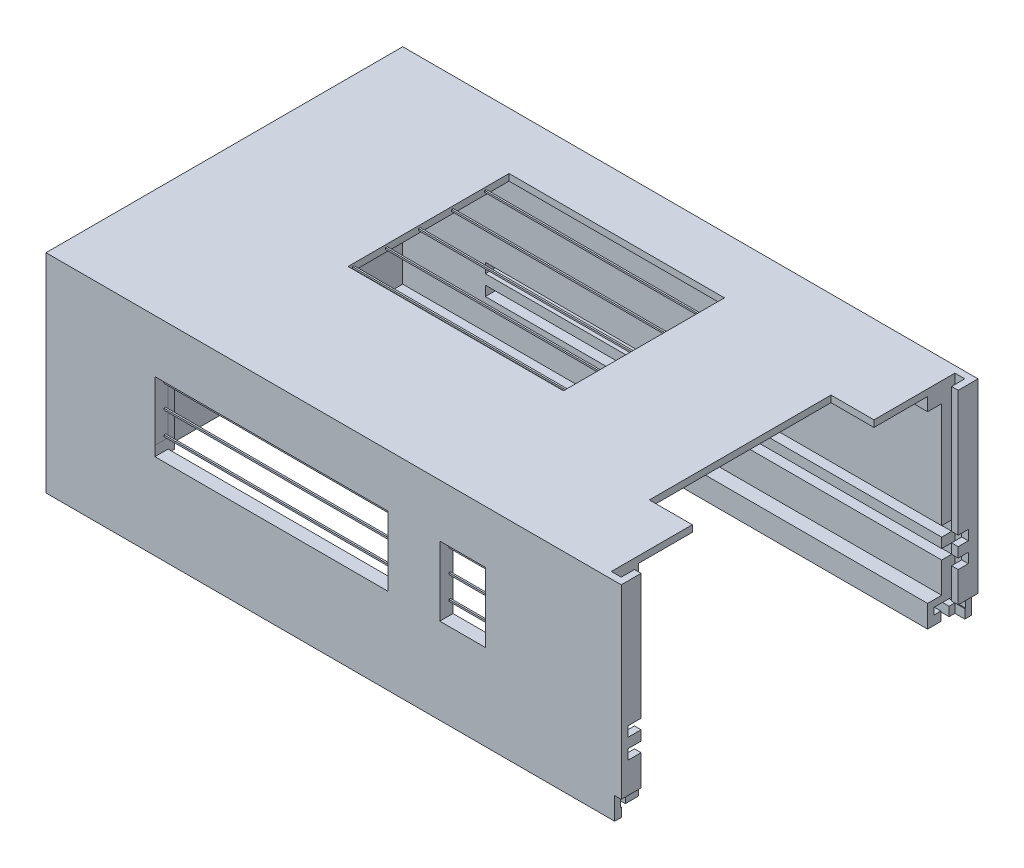
SolidWorks part; units mm, degrees
ref_plane "정면" through (0, 0, 0) normal (0, 0, 1) x (1, 0, 0)
ref_plane "윗면" through (0, 0, 0) normal (0, 1, 0) x (1, 0, 0)
ref_plane "우측면" through (0, 0, 0) normal (1, 0, 0) x (0, 0, -1)
sketch "스케치1" plane through (0, 0, 0) normal (0, 1, 0) x (1, 0, 0)
  line L1 (-87.075, 54) -> (87.075, 54)
  line L2 (-87.075, 54) -> (-87.075, -54)
  line L3 (-87.075, -54) -> (87.075, -54)
  line L4 (87.075, 54) -> (87.075, -54)
  line L5 (-87.075, 54) -> (87.075, -54) construction
  line L6 (-87.075, -54) -> (87.075, 54) construction
  point P0 (0, 0)
  dimension "D1" = 174.15
  dimension "D2" = 108
extrude "보스-돌출1" add sketch "스케치1" along normal blind 63
sketch "스케치4" plane through (87.075, 0, 0) normal (1, 0, 0) x (0, 0, -1)
  line L0 (-50, 0) -> (-50, 3)
  line L1 (-54, 0) -> (54, 0) construction
  line L2 (-50, 3) -> (-52, 3)
  line L3 (-52, 3) -> (-52, 4.5)
  line L4 (-52, 4.5) -> (-46, 4.5)
  line L5 (-46, 4.5) -> (-46, 3)
  line L6 (-46, 3) -> (-48, 3)
  line L7 (-48, 3) -> (-48, 0)
  line L8 (-48, 0) -> (-50, 0)
  line L10 (-54, 63) -> (-54, 0) construction
  line L11 (-50.25, 0) -> (-50.25, 2.75)
  line L12 (-50.25, 2.75) -> (-52.25, 2.75)
  line L13 (-52.25, 2.75) -> (-52.25, 4.75)
  line L14 (-52.25, 4.75) -> (-45.75, 4.75)
  line L15 (-45.75, 4.75) -> (-45.75, 2.75)
  line L16 (-45.75, 2.75) -> (-47.75, 2.75)
  line L17 (-47.75, 2.75) -> (-47.75, 0)
  line L18 (-50, 0) -> (-50.25, 0)
  line L19 (-48, 0) -> (-47.75, 0)
  dimension "D1" = 3
  dimension "D2" = 2
  dimension "D3" = 2
  dimension "D4" = 6
  dimension "D5" = 2
  dimension "D6" = 1.5
  dimension "D7" = 1.5
  dimension "D8" = 0.25
sketch "스케치5" plane through (-87.075, 0, 0) normal (-1, 0, 0) x (0, 0, 1)
  line L0 (50, 0) -> (50, 3) construction
  line L1 (50, 3) -> (52, 3) construction
  line L2 (52, 3) -> (52, 4.5) construction
  line L3 (52, 4.5) -> (46, 4.5) construction
  line L4 (46, 4.5) -> (46, 3) construction
  line L5 (46, 3) -> (48, 3) construction
  line L6 (48, 3) -> (48, 0) construction
  line L7 (48, 0) -> (50, 0) construction
  line L8 (50, 0) -> (50.25, 0) construction
  line L9 (50.25, 0) -> (50.25, 2.75) construction
  line L10 (50.25, 2.75) -> (52.25, 2.75) construction
  line L11 (52.25, 2.75) -> (52.25, 4.75) construction
  line L12 (52.25, 4.75) -> (45.75, 4.75) construction
  line L13 (45.75, 4.75) -> (45.75, 2.75) construction
  line L14 (45.75, 2.75) -> (47.75, 2.75) construction
  line L15 (47.75, 2.75) -> (47.75, 0) construction
  line L16 (48, 0) -> (47.75, 0) construction
  line L17 (50, 0) -> (50, 3)
  line L18 (50, 3) -> (52, 3)
  line L19 (52, 3) -> (52, 4.5)
  line L20 (52, 4.5) -> (46, 4.5)
  line L21 (46, 4.5) -> (46, 3)
  line L22 (46, 3) -> (48, 3)
  line L23 (48, 3) -> (48, 0)
  line L24 (48, 0) -> (50, 0)
  line L25 (50, 0) -> (50.25, 0)
  line L26 (50.25, 0) -> (50.25, 2.75)
  line L27 (50.25, 2.75) -> (52.25, 2.75)
  line L28 (52.25, 2.75) -> (52.25, 4.75)
  line L29 (52.25, 4.75) -> (45.75, 4.75)
  line L30 (45.75, 4.75) -> (45.75, 2.75)
  line L31 (45.75, 2.75) -> (47.75, 2.75)
  line L32 (47.75, 2.75) -> (47.75, 0)
  line L33 (48, 0) -> (47.75, 0)
  line L34 (0, 0) -> (0, 63) construction
  line L35 (-54, 63) -> (54, 63) construction
  line L36 (-48, 0) -> (-47.75, 0)
  line L37 (-47.75, 2.75) -> (-47.75, 0)
  line L38 (-45.75, 2.75) -> (-47.75, 2.75)
  line L39 (-45.75, 4.75) -> (-45.75, 2.75)
  line L40 (-52.25, 4.75) -> (-45.75, 4.75)
  line L41 (-52.25, 2.75) -> (-52.25, 4.75)
  line L42 (-50.25, 2.75) -> (-52.25, 2.75)
  line L43 (-50.25, 0) -> (-50.25, 2.75)
  line L44 (-50, 0) -> (-50.25, 0)
  line L45 (-48, 0) -> (-50, 0)
  line L46 (-48, 3) -> (-48, 0)
  line L47 (-46, 3) -> (-48, 3)
  line L48 (-46, 4.5) -> (-46, 3)
  line L49 (-52, 4.5) -> (-46, 4.5)
  line L50 (-52, 3) -> (-52, 4.5)
  line L51 (-50, 3) -> (-52, 3)
  line L52 (-50, 0) -> (-50, 3)
  line M2 (-54, 0) -> (54, 0)
extrude "컷-돌출2" cut sketch "스케치5" against normal up to surface (174.15 mm away) contours L52 L51 L50 L49 L48 L47 L46 L37 L38 L39 L40 L41 L42 L43 M2 | L52 L46 L47 L48 L49 L50 L51 M2 | L31 L32 L23 L22 L21 L20 L19 L18 L17 L26 L27 L28 L29 L30 M2 | L22 L23 L17 L18 L19 L20 L21 M2 up to face at (87.075, 31.5, 0)
sketch "스케치6" plane through (0, 0, 0) normal (0, -1, 0) x (1, 0, 0)
  line L0 (87.075, -54) -> (-87.075, -54) construction
  line L1 (-87.075, 54) -> (-85.075, 54)
  line L2 (-87.075, 54) -> (-87.075, -54)
  line L3 (-87.075, -54) -> (-85.075, -54)
  line L4 (-85.075, 54) -> (-85.075, -54)
  dimension "D1" = 2
extrude "컷-돌출3" cut sketch "스케치6" against normal up to surface (4.75 mm away) up to face at (0, 4.75, 49)
sketch "스케치7" plane through (87.075, 0, 0) normal (1, 0, 0) x (0, 0, -1)
  line L0 (-54, 63) -> (-54, 0) construction
  line L1 (-48, 57) -> (48, 57)
  line L2 (-48, 57) -> (-48, 6.75)
  line L3 (-48, 6.75) -> (48, 6.75)
  line L4 (48, 57) -> (48, 6.75)
  line L5 (54, 63) -> (54, 0) construction
  line L6 (45.75, 4.75) -> (52.25, 4.75) construction
  line L7 (-54, 63) -> (54, 63) construction
  dimension "D1" = 6
  dimension "D2" = 6
  dimension "D3" = 2
  dimension "D4" = 6
extrude "컷-돌출5" cut sketch "스케치7" against normal blind 168.15
sketch "스케치8" plane through (87.075, 0, 0) normal (1, 0, 0) x (0, 0, -1)
  line L0 (-48, 6.75) -> (48, 6.75) construction
  line L1 (-43.75, 6.75) -> (43.75, 6.75)
  line L2 (-43.75, 6.75) -> (-43.75, 2)
  line L3 (-43.75, 2) -> (43.75, 2)
  line L4 (43.75, 6.75) -> (43.75, 2)
  line L5 (-45.75, 2.75) -> (-45.75, 4.75) construction
  line L6 (-47.75, 0) -> (47.75, 0) construction
  line L7 (45.75, 2.75) -> (45.75, 4.75) construction
  dimension "D1" = 2
  dimension "D2" = 2
  dimension "D3" = 2
extrude "컷-돌출6" cut sketch "스케치8" against normal blind 168.15
sketch "스케치10" plane through (0, 2, 0) normal (0, 1, 0) x (1, 0, 0)
  line L4 (87.075, -43.75) -> (87.075, 43.75)
  line L5 (87.075, 43.75) -> (-81.075, 43.75)
  line L6 (-81.075, 43.75) -> (-81.075, -43.75)
  line L7 (-81.075, -43.75) -> (87.075, -43.75)
  line L8 (87.075, -43.75) -> (87.075, 43.75)
  line L9 (87.075, 43.75) -> (-81.075, 43.75)
  line L10 (-81.075, 43.75) -> (-81.075, -43.75)
  line L11 (-81.075, -43.75) -> (87.075, -43.75)
  dimension "D1" = 0
extrude "컷-돌출8" cut sketch "스케치10" along normal blind 59
ref_plane "평면1" through (0, 24, 0) normal (0, -1, 0) x (-1, 0, 0)
sketch "스케치12" plane through (0, 24, 0) normal (0, -1, 0) x (-1, 0, 0)
  line L1 (-87.075, 48) -> (81.075, 48)
  line L2 (-87.075, 48) -> (-87.075, -48)
  line L3 (-87.075, -48) -> (81.075, -48)
  line L4 (81.075, 48) -> (81.075, -48)
extrude "보스-돌출2" add sketch "스케치12" along normal blind 2
sketch "스케치15" plane through (0, 2, 0) normal (0, 1, 0) x (1, 0, 0)
  line L0 (-81.075, -43.75) -> (87.075, -43.75) construction
  line L1 (-81.075, 43.75) -> (-56.075, 43.75)
  line L2 (-81.075, 43.75) -> (-81.075, -26.25)
  line L3 (-81.075, -26.25) -> (-56.075, -26.25)
  line L4 (-56.075, 43.75) -> (-56.075, -26.25)
  line L5 (-36.7332, -43.75) -> (18.2668, -43.75)
  line L6 (-36.7332, -43.75) -> (-36.7332, -23.75)
  line L7 (-36.7332, -23.75) -> (18.2668, -23.75)
  line L8 (18.2668, -43.75) -> (18.2668, -23.75)
  line L9 (-81.075, 43.75) -> (87.075, 43.75) construction
  line L10 (42.6769, 43.75) -> (87.075, 43.75)
  line L11 (42.6769, 43.75) -> (42.6769, -43.75)
  line L12 (42.6769, -43.75) -> (87.075, -43.75)
  line L13 (87.075, 43.75) -> (87.075, -43.75)
  dimension "D1" = 25
  dimension "D2" = 70
  dimension "D3" = 20
  dimension "D4" = 55
extrude "컷-돌출9" cut sketch "스케치15" against normal blind 2
sketch "스케치16" plane through (0, 24, 0) normal (0, 1, 0) x (1, 0, 0)
  line L0 (87.075, -48) -> (-81.075, -48) construction
  line L1 (-81.075, 48) -> (-56.075, 48)
  line L2 (-81.075, 48) -> (-81.075, -48)
  line L3 (-81.075, -48) -> (-56.075, -48)
  line L4 (-56.075, 48) -> (-56.075, -48)
  line L5 (-81.075, 48) -> (87.075, 48) construction
  line L6 (54.7915, 48) -> (87.075, 48)
  line L7 (54.7915, 48) -> (54.7915, -48)
  line L8 (54.7915, -48) -> (87.075, -48)
  line L9 (87.075, 48) -> (87.075, -48)
  dimension "D1" = 25
extrude "컷-돌출10" cut sketch "스케치16" against normal blind 2
sketch "스케치17" plane through (0, 24, 0) normal (0, 1, 0) x (1, 0, 0)
  line L0 (54.7915, -48) -> (-56.075, -48) construction
  line L1 (-56.075, 48) -> (-54.075, 48)
  line L2 (-56.075, 48) -> (-56.075, -48)
  line L3 (-56.075, -48) -> (-54.075, -48)
  line L4 (-54.075, 48) -> (-54.075, -48)
  dimension "D1" = 2
extrude "보스-돌출3" add sketch "스케치17" along normal blind 5
sketch "스케치18" plane through (0, 2, 0) normal (0, 1, 0) x (1, 0, 0)
  line L0 (-81.075, -43.75) -> (87.075, -43.75) construction
  line L1 (-56.075, 43.75) -> (-54.075, 43.75)
  line L2 (-56.075, 43.75) -> (-56.075, -43.75)
  line L3 (-56.075, -43.75) -> (-54.075, -43.75)
  line L4 (-54.075, 43.75) -> (-54.075, -43.75)
  dimension "D1" = 2
extrude "보스-돌출4" add sketch "스케치18" along normal blind 5
sketch "스케치19" plane through (0, 0, 48) normal (0, 0, -1) x (-1, 0, 0)
  line L0 (54.075, 29) -> (54.075, 24) construction
  line L1 (54.075, 29) -> (-45.925, 29)
  line L2 (54.075, 29) -> (54.075, 47)
  line L3 (54.075, 47) -> (-45.925, 47)
  line L4 (-45.925, 29) -> (-45.925, 47)
  line L5 (-54.7915, 24) -> (54.075, 24) construction
  dimension "D1" = 5
  dimension "D2" = 100
  dimension "D3" = 18
extrude "컷-돌출11" cut sketch "스케치19" against normal blind 6
sketch "스케치23" plane through (0, 63, 0) normal (0, 1, 0) x (1, 0, 0)
  line L5 (-37.7431, 36.8539) -> (27.4625, 36.8539)
  line L6 (-37.7431, 36.8539) -> (-37.7431, -11.8908)
  line L7 (-37.7431, -11.8908) -> (27.4625, -11.8908)
  line L8 (27.4625, 36.8539) -> (27.4625, -11.8908)
extrude "컷-돌출13" cut sketch "스케치23" against normal blind 2
sketch "스케치26" plane through (0, 63, 0) normal (0, 1, 0) x (1, 0, 0)
  line L0 (87.075, 54) -> (-87.075, 54) construction
  line L1 (82.075, 52) -> (85.075, 52)
  line L2 (82.075, 52) -> (82.075, -52)
  line L3 (82.075, -52) -> (85.075, -52)
  line L4 (85.075, 52) -> (85.075, 48)
  line L5 (-87.075, -54) -> (87.075, -54) construction
  line L6 (87.075, -54) -> (87.075, 54) construction
  line L7 (85.075, -48) -> (85.075, -52)
  line L8 (87.075, 48) -> (85.075, 48)
  line L9 (87.075, 48) -> (87.075, -48)
  line L10 (87.075, -48) -> (85.075, -48)
  point P6 (83.575, -52)
  dimension "D1" = 3
  dimension "D2" = 2
  dimension "D3" = 2
  dimension "D4" = 2
  dimension "D5" = 6
  dimension "D6" = 6
extrude "컷-돌출14" cut sketch "스케치26" against normal up to surface (63 mm away)
sketch "스케치28" plane through (0, 4.75, 0) normal (0, -1, 0) x (1, 0, 0)
  line L0 (87.075, 52.25) -> (-85.075, 52.25) construction
  line L1 (87.075, 48) -> (85.075, 48)
  line L2 (87.075, 48) -> (87.075, 52.25)
  line L3 (87.075, 52.25) -> (85.075, 52.25)
  line L4 (85.075, 48) -> (85.075, 52.25)
  line L5 (87.075, -52.25) -> (-85.075, -52.25) construction
  line L6 (87.075, -48) -> (85.075, -48)
  line L7 (87.075, -48) -> (87.075, -52.25)
  line L8 (87.075, -52.25) -> (85.075, -52.25)
  line L9 (85.075, -48) -> (85.075, -52.25)
extrude "보스-돌출6" add sketch "스케치28" along normal up to surface (4.75 mm away) up to face at (42.2875, 0, 51.625)
sketch "스케치29" plane through (0, 63, 0) normal (0, 1, 0) x (1, 0, 0)
  line L0 (82.325, 51.5) -> (84.825, 51.5)
  line L1 (82.325, 51.5) -> (82.325, -51.5)
  line L2 (82.325, -51.5) -> (84.825, -51.5)
  line L3 (84.825, 51.5) -> (84.825, -51.5)
  line L4 (84.825, 47.5) -> (86.825, 47.5)
  line L5 (84.825, 47.5) -> (84.825, -47.5)
  line L6 (84.825, -47.5) -> (86.825, -47.5)
  line L7 (86.825, 47.5) -> (86.825, -47.5)
  line L8 (85.075, 52) -> (82.075, 52) construction
  line L9 (82.075, 52) -> (82.075, -52) construction
  dimension "D1" = 2.5
  dimension "D2" = 4
  dimension "D3" = 0.5
  dimension "D4" = 0.25
sketch "스케치31" plane through (0, 63, 0) normal (0, 1, 0) x (1, 0, 0)
  line L1 (69.075, 27.5) -> (82.075, 27.5)
  line L2 (69.075, 27.5) -> (69.075, -27.5)
  line L3 (69.075, -27.5) -> (82.075, -27.5)
  line L4 (82.075, 27.5) -> (82.075, -27.5)
  line L5 (87.075, 54) -> (-87.075, 54) construction
  line L6 (82.075, 52) -> (82.075, -52) construction
  dimension "D1" = 13
  dimension "D2" = 55
  dimension "D3" = 26.5
extrude "컷-돌출15" cut sketch "스케치31" against normal blind 10
sketch "스케치34" plane through (87.075, 0, 0) normal (1, 0, 0) x (0, 0, -1)
  line L0 (-54, 63) -> (-54, 0) construction
  line L1 (-52, 22) -> (51.0709, 22)
  line L2 (-52, 22) -> (-52, 25)
  line L3 (-52, 25) -> (51.0709, 25)
  line L4 (51.0709, 22) -> (51.0709, 25)
  dimension "D1" = 2
  dimension "D2" = 3
extrude "컷-돌출16" cut sketch "스케치34" against normal blind 143.15 contours L3 L4 L1 L2
sketch "스케치36" plane through (87.075, 0, 0) normal (1, 0, 0) x (0, 0, -1)
  line L0 (-52, 23.5) -> (51.0709, 23.5)
  line L1 (-52, 22) -> (-52, 25) construction
  line L2 (51.0709, 22) -> (51.0709, 25) construction
  dimension "D1" = 103.0709
sketch "스케치37" plane through (-54.075, 0, 0) normal (1, 0, 0) x (0, 0, -1)
  line L1 (-48, 29) -> (48, 29)
  line L2 (-48, 29) -> (-48, 25)
  line L3 (-48, 25) -> (48, 25)
  line L4 (48, 29) -> (48, 25)
extrude "컷-돌출17" cut sketch "스케치37" against normal blind 10
sketch "스케치38" plane through (0, 2, 0) normal (0, 1, 0) x (1, 0, 0)
  line L1 (42.6769, -43.75) -> (-81.075, -43.75)
  line L2 (42.6769, -43.75) -> (42.6769, 43.75)
  line L3 (42.6769, 43.75) -> (-81.075, 43.75)
  line L4 (-81.075, -43.75) -> (-81.075, 43.75)
extrude "컷-돌출18" cut sketch "스케치38" against normal blind 10
sketch "스케치42" plane through (87.075, 0, 0) normal (1, 0, 0) x (0, 0, -1)
  line L0 (48, 25) -> (51.0709, 25) construction
  line L1 (-52, 19) -> (51.0709, 19)
  line L2 (-52, 19) -> (-52, 16)
  line L3 (-52, 16) -> (51.0709, 16)
  line L4 (51.0709, 19) -> (51.0709, 16)
  point P6 (49.5355, 25)
  dimension "D1" = 3
  dimension "D2" = 6
extrude "컷-돌출20" cut sketch "스케치42" against normal up to surface (143.15 mm away) up to face at (-56.075, 23.5, -49.5355)
sketch "스케치45" plane through (0, 0, 48) normal (0, 0, -1) x (-1, 0, 0)
  line L1 (-45.925, 29) -> (54.109, 29)
  line L2 (-45.925, 29) -> (-45.925, 26)
  line L3 (-45.925, 26) -> (54.109, 26)
  line L4 (54.109, 29) -> (54.109, 26)
  dimension "D1" = 3
extrude "컷-돌출21" cut sketch "스케치45" against normal up to surface (6 mm away) up to face at (-4.075, 38, 54)
sketch "스케치46" plane through (0, 26, 0) normal (0, 1, 0) x (1, 0, 0)
  line L0 (45.925, -48) -> (-54.109, -48) construction
  line L1 (16.5347, -48) -> (32.1394, -48)
  line L2 (16.5347, -48) -> (16.5347, -54)
  line L3 (16.5347, -54) -> (32.1394, -54)
  line L4 (32.1394, -48) -> (32.1394, -54)
  line L5 (-54.109, -54) -> (45.925, -54) construction
extrude "보스-돌출7" add sketch "스케치46" along normal up to surface (21 mm away) up to face at (-4.075, 47, 51)
sketch "스케치47" plane through (0, 0, 48) normal (0, 0, -1) x (-1, 0, 0)
  line L0 (56.075, 25) -> (-82.075, 25) construction
  line L1 (54.109, 25) -> (-45.925, 25)
  line L2 (54.109, 25) -> (54.109, 47)
  line L3 (54.109, 47) -> (-45.925, 47)
  line L4 (-45.925, 25) -> (-45.925, 47)
extrude "컷-돌출22" cut sketch "스케치47" against normal blind 2
sketch "스케치48" plane through (-54.075, 0, 0) normal (1, 0, 0) x (0, 0, -1)
  line L1 (-43.75, 7) -> (43.75, 7)
  line L2 (-43.75, 7) -> (-43.75, 2)
  line L3 (-43.75, 2) -> (43.75, 2)
  line L4 (43.75, 7) -> (43.75, 2)
extrude "컷-돌출23" cut sketch "스케치48" against normal blind 2
sketch "스케치49" plane through (87.075, 0, 0) normal (1, 0, 0) x (0, 0, -1)
  line L0 (-54, 63) -> (-54, 0) construction
  line L1 (-54, 6.75) -> (54, 6.75)
  line L2 (-54, 6.75) -> (-54, 0)
  line L3 (-54, 0) -> (54, 0)
  line L4 (54, 6.75) -> (54, 0)
extrude "컷-돌출24" cut sketch "스케치49" against normal blind 2
sketch "스케치51" plane through (-85.075, 0, 0) normal (-1, 0, 0) x (0, 0, 1)
  line L0 (52.25, 2.75) -> (50.25, 2.75) construction
  line L1 (50.25, 2.75) -> (50.25, 0) construction
  line L2 (50.25, 0) -> (54, 0) construction
  line L3 (54, 0) -> (54, 4.75) construction
  line L4 (54, 4.75) -> (52.25, 4.75) construction
  line L5 (52.25, 4.75) -> (52.25, 2.75) construction
  line L6 (-52.25, 2.75) -> (-52.25, 4.75) construction
  line L7 (-52.25, 4.75) -> (-54, 4.75) construction
  line L8 (-54, 4.75) -> (-54, 0) construction
  line L9 (-54, 0) -> (-50.25, 0) construction
  line L10 (-50.25, 0) -> (-50.25, 2.75) construction
  line L11 (-50.25, 2.75) -> (-52.25, 2.75) construction
  line L12 (47.75, 2.75) -> (45.75, 2.75) construction
  line L13 (45.75, 2.75) -> (45.75, 4.75) construction
  line L14 (45.75, 4.75) -> (-45.75, 4.75) construction
  line L15 (-45.75, 4.75) -> (-45.75, 2.75) construction
  line L16 (-45.75, 2.75) -> (-47.75, 2.75) construction
  line L17 (-47.75, 2.75) -> (-47.75, 0) construction
  line L18 (-47.75, 0) -> (47.75, 0) construction
  line L19 (47.75, 0) -> (47.75, 2.75) construction
  line L20 (52.25, 2.75) -> (50.25, 2.75)
  line L21 (50.25, 2.75) -> (50.25, 0)
  line L22 (50.25, 0) -> (54, 0)
  line L23 (54, 0) -> (54, 4.75)
  line L24 (54, 4.75) -> (52.25, 4.75)
  line L25 (52.25, 4.75) -> (52.25, 2.75)
  line L26 (-52.25, 2.75) -> (-52.25, 4.75)
  line L27 (-52.25, 4.75) -> (-54, 4.75)
  line L28 (-54, 4.75) -> (-54, 0)
  line L29 (-54, 0) -> (-50.25, 0)
  line L30 (-50.25, 0) -> (-50.25, 2.75)
  line L31 (-50.25, 2.75) -> (-52.25, 2.75)
  line L32 (47.75, 2.75) -> (45.75, 2.75)
  line L33 (45.75, 2.75) -> (45.75, 4.75)
  line L34 (45.75, 4.75) -> (-45.75, 4.75)
  line L35 (-45.75, 4.75) -> (-45.75, 2.75)
  line L36 (-45.75, 2.75) -> (-47.75, 2.75)
  line L37 (-47.75, 2.75) -> (-47.75, 0)
  line L38 (-47.75, 0) -> (47.75, 0)
  line L39 (47.75, 0) -> (47.75, 2.75)
extrude "보스-돌출8" add sketch "스케치51" along normal up to surface (2 mm away) up to face at (-87.075, 33.875, 0)
sketch "스케치54" plane through (-37.7431, 0, 0) normal (1, 0, 0) x (0, 0, -1)
  line L0 (36.8539, 63) -> (-11.8908, 63) construction
  line L1 (-10.5364, 62.25) -> (-10.0364, 62.25)
  line L2 (-10.5364, 62.25) -> (-10.5364, 61.75)
  line L3 (-10.5364, 61.75) -> (-10.0364, 61.75)
  line L4 (-10.0364, 62.25) -> (-10.0364, 61.75)
  line L5 (-0.5364, 62.25) -> (-0.0364, 62.25)
  line L6 (-0.5364, 62.25) -> (-0.5364, 61.75)
  line L7 (-0.5364, 61.75) -> (-0.0364, 61.75)
  line L8 (-0.0364, 62.25) -> (-0.0364, 61.75)
  line L9 (9.4636, 62.25) -> (9.9636, 62.25)
  line L10 (9.4636, 62.25) -> (9.4636, 61.75)
  line L11 (9.4636, 61.75) -> (9.9636, 61.75)
  line L12 (9.9636, 62.25) -> (9.9636, 61.75)
  line L13 (19.4636, 62.25) -> (19.9636, 62.25)
  line L14 (19.4636, 62.25) -> (19.4636, 61.75)
  line L15 (19.4636, 61.75) -> (19.9636, 61.75)
  line L16 (19.9636, 62.25) -> (19.9636, 61.75)
  line L17 (29.4636, 62.25) -> (29.9636, 62.25)
  line L18 (29.4636, 62.25) -> (29.4636, 61.75)
  line L19 (29.4636, 61.75) -> (29.9636, 61.75)
  line L20 (29.9636, 62.25) -> (29.9636, 61.75)
  dimension "D1" = 0.5
  dimension "D2" = 0.5
  dimension "D3" = 0.75
  dimension "D4" = 5
extrude "보스-돌출10" add sketch "스케치54" along normal up to surface (65.2056 mm away) up to face at (27.4625, 62, -12.4816)
sketch "스케치55" plane through (45.925, 0, 0) normal (-1, 0, 0) x (0, 0, 1)
  line L0 (48, 47) -> (48, 25) construction
  line L1 (50.75, 44.3525) -> (51.25, 44.3525)
  line L2 (50.75, 44.3525) -> (50.75, 43.8525)
  line L3 (50.75, 43.8525) -> (51.25, 43.8525)
  line L4 (51.25, 44.3525) -> (51.25, 43.8525)
  line L5 (50.75, 37.3525) -> (51.25, 37.3525)
  line L6 (50.75, 37.3525) -> (50.75, 36.8525)
  line L7 (50.75, 36.8525) -> (51.25, 36.8525)
  line L8 (51.25, 37.3525) -> (51.25, 36.8525)
  line L9 (50.75, 30.3525) -> (51.25, 30.3525)
  line L10 (50.75, 30.3525) -> (50.75, 29.8525)
  line L11 (50.75, 29.8525) -> (51.25, 29.8525)
  line L12 (51.25, 30.3525) -> (51.25, 29.8525)
  dimension "D1" = 0.5
  dimension "D2" = 0.5
  dimension "D3" = 2.75
  dimension "D4" = 3
extrude "보스-돌출11" add sketch "스케치55" along normal up to surface (133 mm away) up to face at (-87.075, 8.35, 0)
